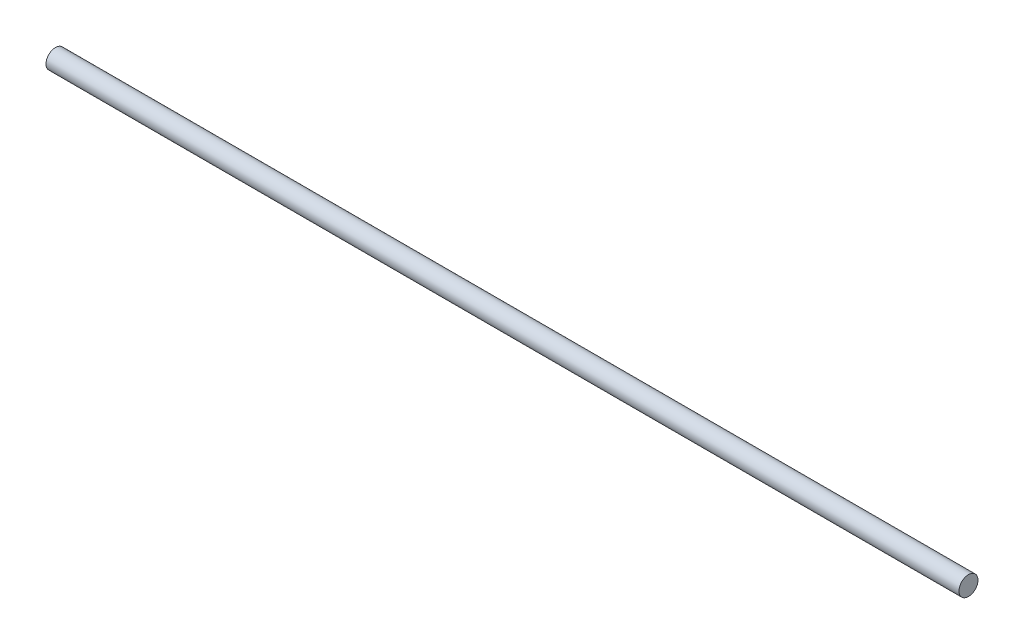
SolidWorks part; units mm, degrees
ref_plane "Plan de face" through (0, 0, 0) normal (0, 0, 1) x (1, 0, 0)
ref_plane "Plan de dessus" through (0, 0, 0) normal (0, 1, 0) x (1, 0, 0)
ref_plane "Plan de droite" through (0, 0, 0) normal (1, 0, 0) x (0, 0, -1)
sketch "Esquisse1" plane through (0, 0, 0) normal (0, 0, 1) x (1, 0, 0)
  line L0 (-304.8, 3.175) -> (-304.8, 0)
  line L1 (-304.8, 0) -> (0, 0)
  line L2 (0, 0) -> (0, 3.175)
  line L3 (0, 3.175) -> (-304.8, 3.175)
  line L4 (-304.8, 0) -> (0, 0) construction
  dimension "D1" = 3.175
  dimension "D2" = 304.8
revolve "Révolution1" add sketch "Esquisse1" angle 360 about L4
